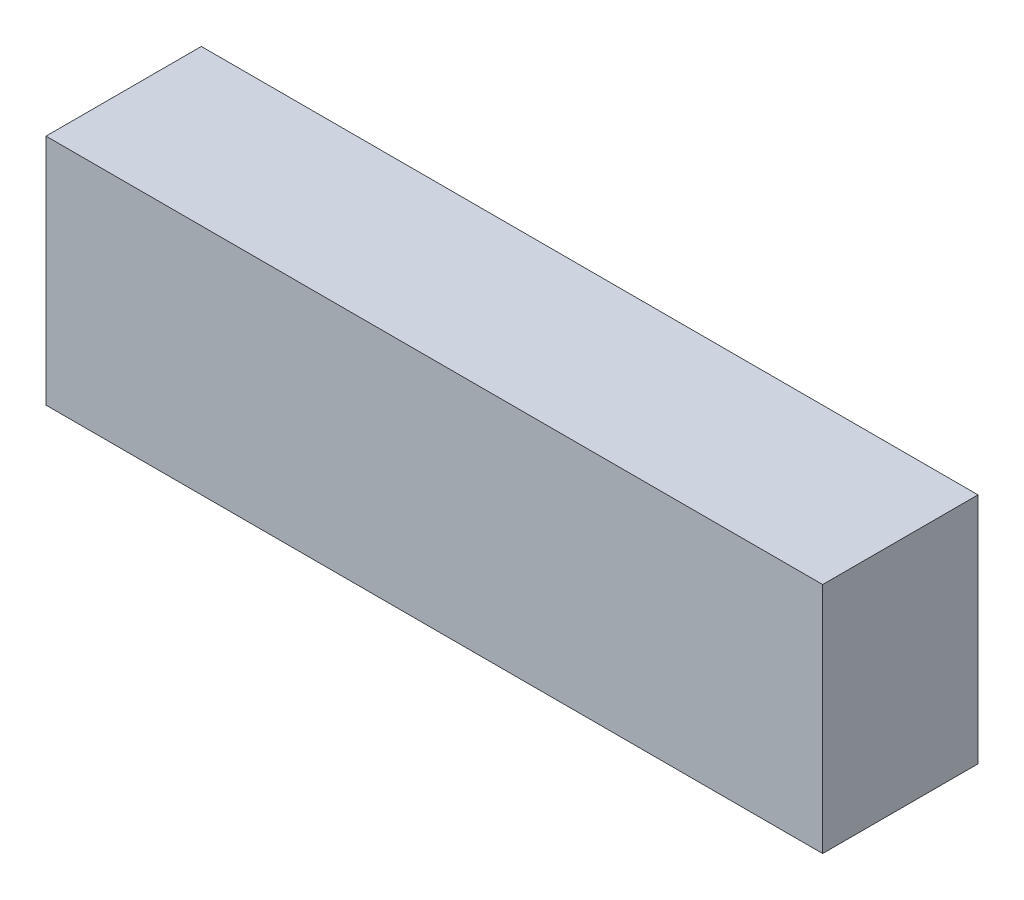
SolidWorks part; units mm, degrees
ref_plane "Alzado" through (0, 0, 0) normal (0, 0, 1) x (1, 0, 0)
ref_plane "Planta" through (0, 0, 0) normal (0, 1, 0) x (1, 0, 0)
ref_plane "Vista lateral" through (0, 0, 0) normal (1, 0, 0) x (0, 0, -1)
sketch "Croquis1" plane through (0, 0, 0) normal (0, 0, 1) x (1, 0, 0)
  line L1 (127, -38.1) -> (-127, -38.1)
  line L2 (127, -38.1) -> (127, 38.1)
  line L3 (127, 38.1) -> (-127, 38.1)
  line L4 (-127, -38.1) -> (-127, 38.1)
  line L5 (127, -38.1) -> (-127, 38.1) construction
  line L6 (127, 38.1) -> (-127, -38.1) construction
  point P0 (0, 0)
  dimension "D1" = 254
  dimension "D2" = 76.2
extrude "Saliente-Extruir1" add sketch "Croquis1" along normal blind 50.8
